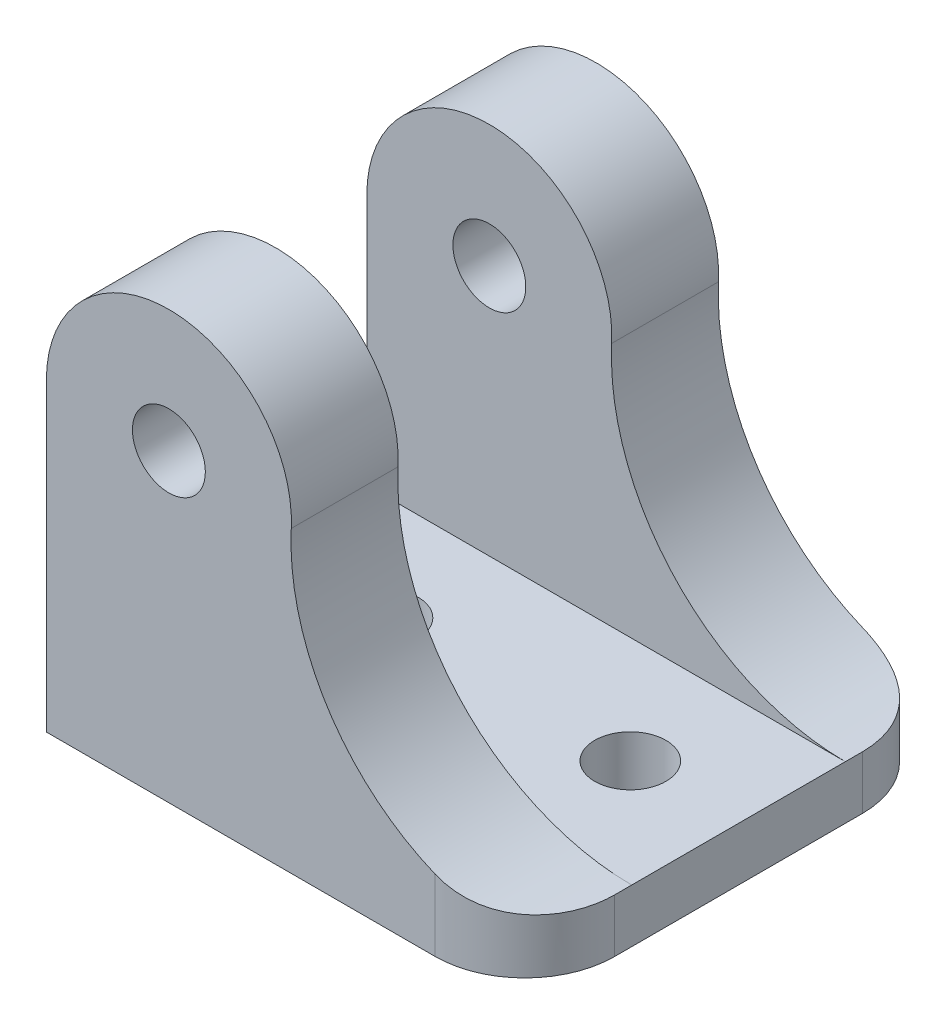
SolidWorks part; units mm, degrees
ref_plane "Front" through (0, 0, 0) normal (0, 0, 1) x (1, 0, 0)
ref_plane "Top" through (0, 0, 0) normal (0, 1, 0) x (1, 0, 0)
ref_plane "Right" through (0, 0, 0) normal (1, 0, 0) x (0, 0, -1)
sketch "Sketch1" plane through (0, 0, 0) normal (0, 1, 0) x (1, 0, 0)
  line L1 (21.336, -19.05) -> (-21.336, -19.05)
  line L2 (21.336, -19.05) -> (21.336, 19.05)
  line L3 (21.336, 19.05) -> (-21.336, 19.05)
  line L4 (-21.336, -19.05) -> (-21.336, 19.05)
  line L5 (21.336, -19.05) -> (-21.336, 19.05) construction
  line L6 (21.336, 19.05) -> (-21.336, -19.05) construction
  point P0 (0, 0)
  dimension "D1" = 38.1
  dimension "D2" = 42.672
extrude "Boss-Extrude1" add sketch "Sketch1" along normal blind 4.7625
sketch "Sketch2" plane through (0, 0, 19.05) normal (0, 0, 1) x (1, 0, 0)
  line L0 (-21.336, 4.7625) -> (-21.336, 27.178)
  line L1 (-21.336, 4.7625) -> (21.336, 4.7625) construction
  line L2 (-21.336, 0) -> (21.336, 0) construction
  line L3 (21.336, 4.7625) -> (-21.336, 4.7625)
  arc A0 (-21.336, 27.178) -> (0.5015, 26.6432) centre (-10.4107, 27.178) cw
  arc A1 (0.5015, 26.6432) -> (21.336, 4.7625) centre (21.336, 25.6221) ccw
  circle A2 centre (-10.4107, 27.178) radius 3.25
  point P11 (-10.1432, 38.1)
  point P12 (19.1514, 4.7625)
  point P14 (0, 0)
  dimension "D3" = 6.5
  dimension "D1" = 27.178
  dimension "D2" = 38.1
extrude "Boss-Extrude2" add sketch "Sketch2" against normal blind 9.525
mirror "Mirror1" about plane through (0, 0, 0) normal (0, 0, 1) of "Boss-Extrude2"
sketch "Sketch3" plane through (0, 4.7625, 0) normal (0, 1, 0) x (1, 0, 0)
  line L0 (-10.414, 0) -> (0, 0) construction
  line L1 (0, 0) -> (11.684, 0) construction
  line L2 (-21.336, 9.525) -> (-21.336, -9.525) construction
  circle A0 centre (-10.414, 0) radius 3.175
  circle A1 centre (11.684, 0) radius 3.175
  dimension "D1" = 6.35
  dimension "D2" = 10.922
  dimension "D3" = 33.02
extrude "Cut-Extrude1" cut sketch "Sketch3" against normal blind 9.525
fillet "Fillet1" radius 8 2 edges at (21.336, 2.3813, -19.05) (21.336, 2.3812, 19.05)
